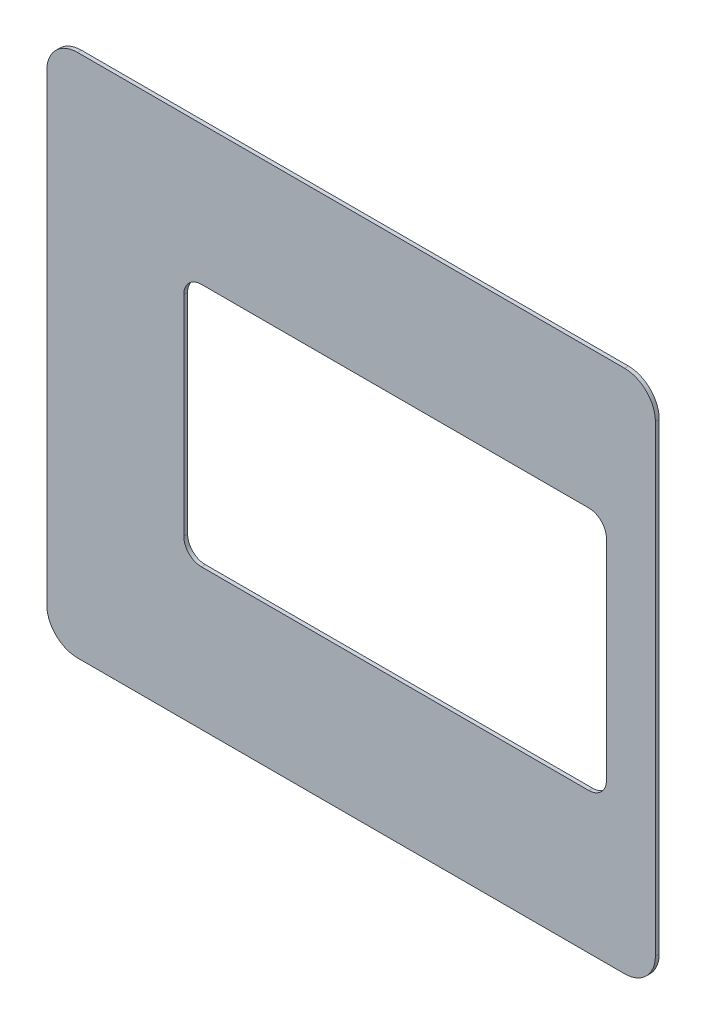
SolidWorks part; units mm, degrees
ref_plane "Front" through (0, 0, 0) normal (0, 0, 1) x (1, 0, 0)
ref_plane "Top" through (0, 0, 0) normal (0, 1, 0) x (1, 0, 0)
ref_plane "Right" through (0, 0, 0) normal (1, 0, 0) x (0, 0, -1)
sketch "Sketch1" plane through (0, 0, 0) normal (0, 0, 1) x (1, 0, 0)
  line L0 (39.5, -34.036) -> (-39.5, 34.036) construction
  line L1 (-39.5, 34.036) -> (39.5, 34.036)
  line L2 (-39.5, 34.036) -> (-39.5, -34.036)
  line L3 (-39.5, -34.036) -> (39.5, -34.036)
  line L4 (39.5, 34.036) -> (39.5, -34.036)
  dimension "D1" = 79
  dimension "D2" = 68.072
extrude "Boss-Extrude1" add sketch "Sketch1" along normal blind 0.5
fillet "Fillet1" radius 4 4 edges at (-39.5, -34.036, 0.25) (39.5, -34.036, 0.25) (39.5, 34.036, 0.25) (-39.5, 34.036, 0.25)
sketch "Sketch2" plane through (0, 0, 0.5) normal (0, 0, 1) x (1, 0, 0)
  line L0 (35.5, 34.036) -> (-35.5, 34.036) construction
  line L1 (-19.428, 16.002) -> (30.864, 16.002)
  line L2 (-21.714, 13.716) -> (-21.714, -13.462)
  line L3 (-19.428, -15.748) -> (30.864, -15.748)
  line L4 (33.15, 13.716) -> (33.15, -13.462)
  line L5 (39.5, -30.036) -> (39.5, 30.036) construction
  arc A1 (33.15, -13.462) -> (30.864, -15.748) centre (30.864, -13.462) cw
  arc A2 (30.864, 16.002) -> (33.15, 13.716) centre (30.864, 13.716) cw
  arc A3 (-19.428, 16.002) -> (-21.714, 13.716) centre (-19.428, 13.716) ccw
  arc A4 (-21.714, -13.462) -> (-19.428, -15.748) centre (-19.428, -13.462) ccw
  point P10 (33.15, 16.002)
  point P15 (-21.714, 16.002)
  point P18 (-21.714, -15.748)
  dimension "D5" = 2.286
  dimension "D1" = 54.864
  dimension "D2" = 31.75
  dimension "D3" = 18.034
  dimension "D4" = 6.35
extrude "Cut-Extrude1" cut sketch "Sketch2" against normal through all
